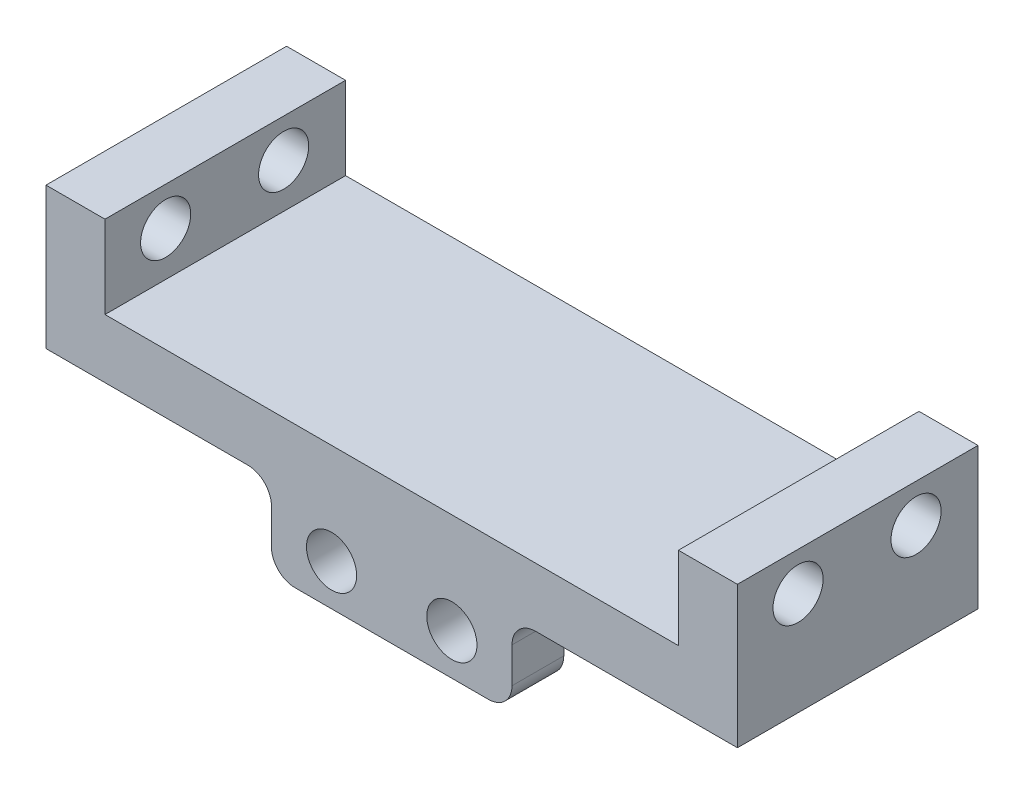
SolidWorks part; units mm, degrees
ref_plane "Front" through (0, 0, 0) normal (0, 0, 1) x (1, 0, 0)
ref_plane "Top" through (0, 0, 0) normal (0, 1, 0) x (1, 0, 0)
ref_plane "Right" through (0, 0, 0) normal (1, 0, 0) x (0, 0, -1)
sketch "Sketch1" plane through (0, 0, 0) normal (0, 1, 0) x (1, 0, 0)
  line L1 (0, 0) -> (58.6, 0)
  line L2 (0, 0) -> (0, 20.3898)
  line L3 (0, 20.3898) -> (58.6, 20.3898)
  line L4 (58.6, 0) -> (58.6, 20.3898)
  dimension "D1" = 58.6
  dimension "D2" = 20.3898
extrude "bracketBase" add sketch "Sketch1" along normal blind 5
sketch "Sketch2" plane through (0, 0, 0) normal (-1, 0, 0) x (0, 0, 1)
  line L0 (0, 5) -> (0, 0) construction
  line L1 (-20.3898, 0) -> (0, 0)
  line L2 (-20.3898, 0) -> (-20.3898, 12)
  line L3 (-20.3898, 12) -> (0, 12)
  line L4 (0, 0) -> (0, 12)
  line L5 (-20.3898, 5) -> (0, 5) construction
  dimension "D1" = 7
extrude "legMountingTab" add sketch "Sketch2" against normal blind 5
sketch "Sketch3" plane through (5, 0, 0) normal (1, 0, 0) x (0, 0, -1)
  line L0 (20.3898, 12) -> (20.3898, 5) construction
  line L1 (0, 12) -> (20.3898, 12) construction
  circle A0 centre (15.1398, 8.75) radius 2.125
  circle A1 centre (5.1398, 8.75) radius 2.125
  dimension "D1" = 4.25
  dimension "D2" = 5.25
  dimension "D3" = 3.25
  dimension "D4" = 10
extrude "legMountingHoles" cut sketch "Sketch3" against normal blind 5
ref_plane "Plane1" through (29.3, 0, 0) normal (-1, 0, 0) x (0, 0, 1)
mirror "legMountingHoles2" about plane through (29.3, 0, 0) normal (-1, 0, 0) of "legMountingHoles", "legMountingTab"
sketch "Sketch4" plane through (0, 0, 0) normal (0, 0, 1) x (1, 0, 0)
  line L0 (0, 0) -> (58.6, 0) construction
  line L1 (39.4949, 0) -> (19.1051, 0)
  line L2 (39.4949, 0) -> (39.4949, -7)
  line L3 (39.4949, -7) -> (19.1051, -7)
  line L4 (19.1051, 0) -> (19.1051, -7)
  point P4 (29.3, 0)
  point P7 (29.3, 0)
  dimension "D1" = 7
  dimension "D2" = 20.3898
extrude "arduinoMountingTab" add sketch "Sketch4" against normal blind 4.3898
sketch "Sketch5" plane through (0, 0, 0) normal (0, 0, 1) x (1, 0, 0)
  line L2 (29.3, -7) -> (29.3, 5) construction
  line L3 (19.1051, -7) -> (39.4949, -7) construction
  line L4 (5, 5) -> (53.6, 5) construction
  line L5 (39.4949, -3.5) -> (29.3, -3.5) construction
  line L8 (39.4949, -7) -> (39.4949, 0) construction
  circle A0 centre (34.3974, -3.5) radius 2.125
  circle A1 centre (24.2026, -3.5) radius 2.125
  dimension "D1" = 4.25
extrude "arduinoMountingHoles" cut sketch "Sketch5" against normal blind 5
fillet "Fillet1" radius 2 4 edges at (19.1051, -7, -2.1949) (39.4949, -7, -2.1949) (39.4949, 0, -2.1949) (19.1051, 0, -2.1949)
